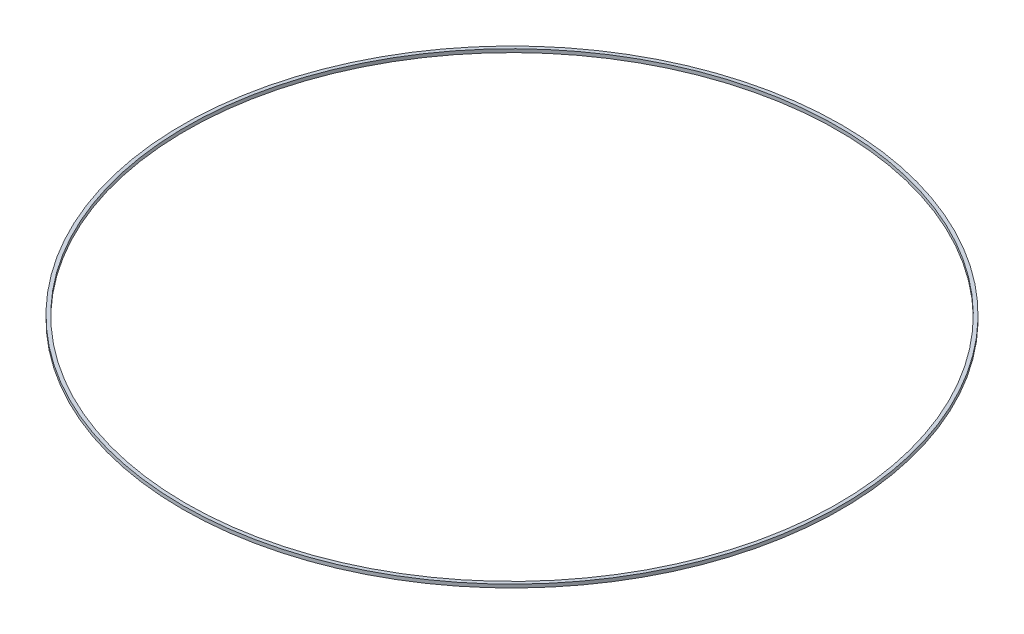
SolidWorks part; units mm, degrees
ref_plane "Front Plane" through (0, 0, 0) normal (0, 0, 1) x (1, 0, 0)
ref_plane "Top Plane" through (0, 0, 0) normal (0, 1, 0) x (1, 0, 0)
ref_plane "Right Plane" through (0, 0, 0) normal (1, 0, 0) x (0, 0, -1)
sketch "Sketch1" plane through (0, 0, 0) normal (0, 1, 0) x (1, 0, 0)
  circle A0 centre (0, 0) radius 123.1465
  circle A1 centre (0, 0) radius 124.4165
  dimension "D1" = 1.27
extrude "Boss-Extrude1" add sketch "Sketch1" along normal blind 1.27
